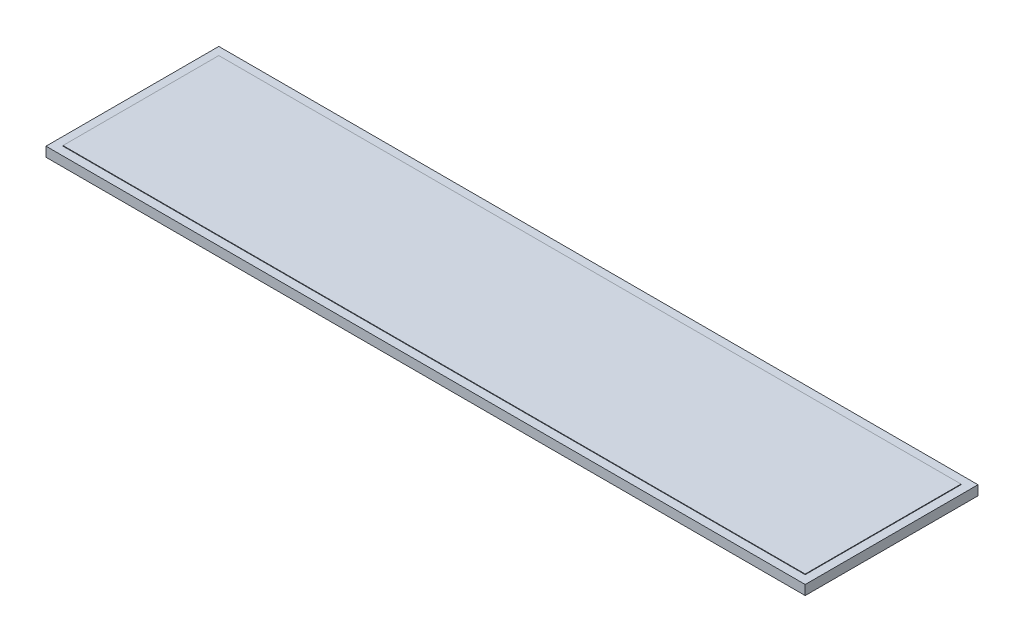
SolidWorks part; units mm, degrees
ref_plane "Спереди" through (0, 0, 0) normal (0, 0, 1) x (1, 0, 0)
ref_plane "Сверху" through (0, 0, 0) normal (0, 1, 0) x (1, 0, 0)
ref_plane "Справа" through (0, 0, 0) normal (1, 0, 0) x (0, 0, -1)
sketch "Эскиз1" plane through (0, 0, 0) normal (0, 1, 0) x (1, 0, 0)
  line L1 (-67, 15.25) -> (67, 15.25)
  line L2 (-67, 15.25) -> (-67, -15.25)
  line L3 (-67, -15.25) -> (67, -15.25)
  line L4 (67, 15.25) -> (67, -15.25)
  line L5 (-67, 15.25) -> (67, -15.25) construction
  line L6 (-67, -15.25) -> (67, 15.25) construction
  point P0 (0, 0)
  dimension "D1" = 134
  dimension "D2" = 30.5
extrude "Бобышка-Вытянуть1" add sketch "Эскиз1" against normal blind 1.8
sketch "Эскиз2" plane through (0, 0, 0) normal (0, 1, 0) x (1, 0, 0)
  line L9 (-65.5, 13.75) -> (-65.5, -13.75)
  line L10 (-65.5, -13.75) -> (65.5, -13.75)
  line L11 (65.5, -13.75) -> (65.5, 13.75)
  line L12 (65.5, 13.75) -> (-65.5, 13.75)
  line L13 (-65.5, 13.75) -> (-65.5, -13.75)
  line L14 (-65.5, -13.75) -> (65.5, -13.75)
  line L15 (65.5, -13.75) -> (65.5, 13.75)
  line L16 (65.5, 13.75) -> (-65.5, 13.75)
  dimension "D1" = 1.5
extrude "Вырез-Вытянуть2" cut sketch "Эскиз2" against normal blind 0.1 flip side to cut
